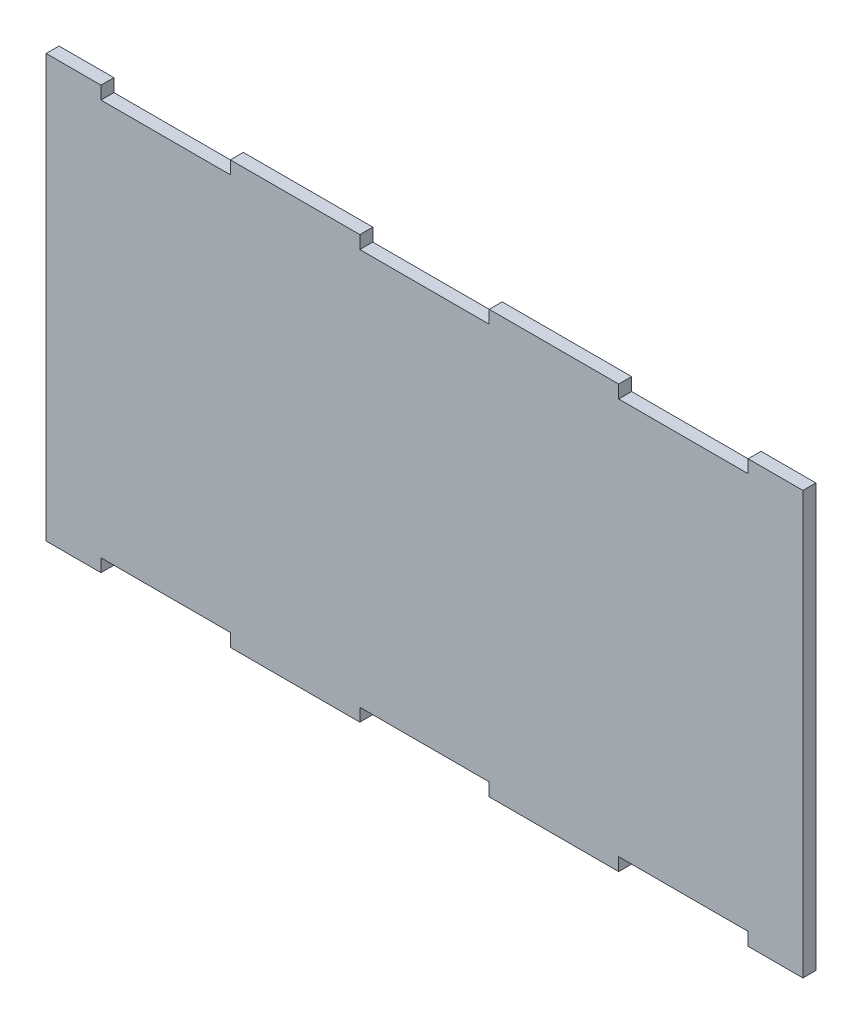
SolidWorks part; units mm, degrees
ref_plane "Front Plane" through (0, 0, 0) normal (0, 0, 1) x (1, 0, 0)
ref_plane "Top Plane" through (0, 0, 0) normal (0, 1, 0) x (1, 0, 0)
ref_plane "Right Plane" through (0, 0, 0) normal (1, 0, 0) x (0, 0, -1)
sketch "Sketch1" plane through (0, 0, 0) normal (0, 0, 1) x (1, 0, 0)
  line L1 (-74.2632, 41.4337) -> (74.2632, 41.4337)
  line L2 (-74.2632, 41.4337) -> (-74.2632, -41.4337)
  line L3 (-74.2632, -41.4337) -> (74.2632, -41.4337)
  line L4 (74.2632, 41.4337) -> (74.2632, -41.4337)
  line L5 (0, -41.4337) -> (0, 41.4337) construction
  line L6 (-74.2632, 0) -> (74.2632, 0) construction
  point P0 (0, 0)
  point P4 (75.057, -26.2272)
  dimension "D1" = 148.5265
  dimension "D2" = 82.8675
extrude "Boss-Extrude1" add sketch "Sketch1" along normal blind 2.54
sketch "Sketch2" plane through (0, 0, 2.54) normal (0, 0, 1) x (1, 0, 0)
  line L0 (74.2632, 41.4337) -> (-74.2632, 41.4337) construction
  line L1 (63.5, 41.4337) -> (38.1, 41.4337)
  line L2 (63.5, 41.4337) -> (63.5, 38.8937)
  line L3 (63.5, 38.8937) -> (38.1, 38.8937)
  line L4 (38.1, 41.4337) -> (38.1, 38.8937)
  line L5 (74.2632, -41.4337) -> (74.2632, 41.4337) construction
  dimension "D1" = 2.54
  dimension "D2" = 25.4
  dimension "D3" = 10.7633
extrude "Cut-Extrude1" cut sketch "Sketch2" against normal through all
pattern_linear "LPattern1" count 3 spacing 50.8 along (-1, 0, 0) of "Cut-Extrude1"
mirror "Mirror1" about plane through (0, 0, 0) normal (0, 1, 0) of "LPattern1", "Cut-Extrude1"
